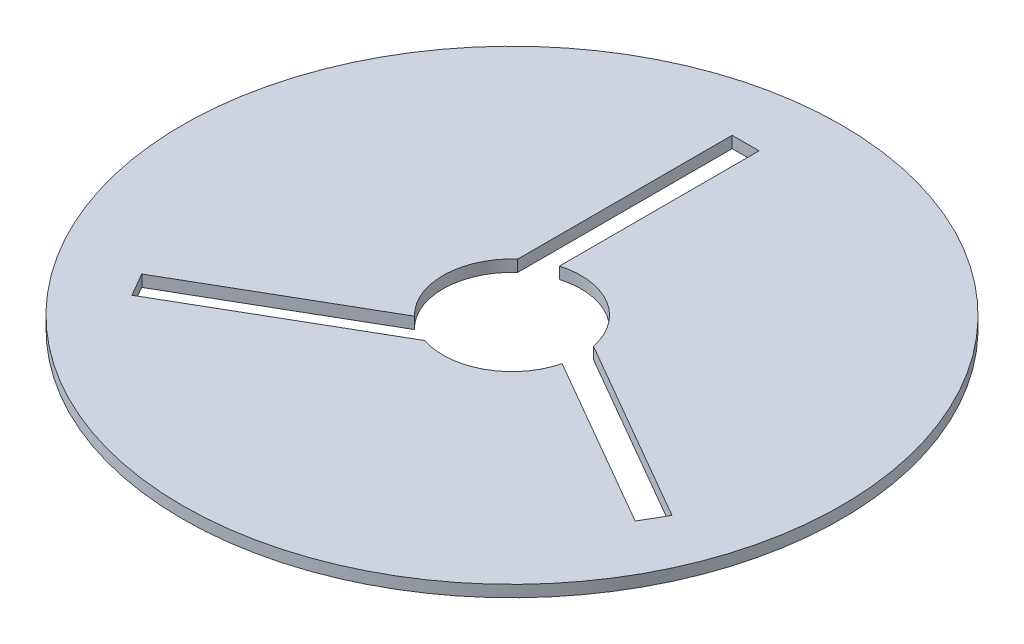
SolidWorks part; units mm, degrees
ref_plane "Alzado" through (0, 0, 0) normal (0, 0, 1) x (1, 0, 0)
ref_plane "Planta" through (0, 0, 0) normal (0, 1, 0) x (1, 0, 0)
ref_plane "Vista lateral" through (0, 0, 0) normal (1, 0, 0) x (0, 0, -1)
sketch "Croquis2" plane through (0, 0, 0) normal (0, 1, 0) x (1, 0, 0)
  line L0 (-11.524, 68.3) -> (-11.524, -4.4)
  line L1 (-11.724, -4.2) -> (-4.974, -4.2)
  line L2 (-5.174, -4.4) -> (-5.174, 68.3)
  line L3 (-5.174, 68.3) -> (-11.524, 68.3)
  line L4 (64.9115, -24.1699) -> (1.9515, 12.1801)
  line L5 (2.2247, 12.2533) -> (-1.1503, 6.4076)
  line L6 (-1.2235, 6.6808) -> (61.7365, -29.6692)
  line L7 (61.7365, -29.6692) -> (64.9115, -24.1699)
  line L8 (-53.3875, -44.1301) -> (9.5725, -7.7801)
  line L9 (-12.0434, -12.6967) -> (6.2975, -2.1076)
  line L10 (6.2975, -2.1076) -> (9.6725, -7.9533)
  line L11 (9.6725, -7.9533) -> (-5.3896, -16.6494)
  line L12 (17.0174, -4.0815) -> (-1.3235, 6.5076)
  line L13 (-1.3235, 6.5076) -> (2.0515, 12.3533)
  line L14 (2.0515, 12.3533) -> (17.1136, 3.6571)
  line L15 (-4.974, 16.7782) -> (-4.974, -4.4)
  line L16 (-4.974, -4.4) -> (-11.724, -4.4)
  line L17 (-11.724, -4.4) -> (-11.724, 12.9922)
  line L18 (9.4993, -8.0533) -> (6.1243, -2.2076)
  line L19 (6.3975, -2.2808) -> (-56.5625, -38.6308)
  line L20 (-56.5625, -38.6308) -> (-53.3875, -44.1301)
  line L21 (-8.349, 3.8) -> (-8.349, -4.2) construction
  line L22 (0.5372, 9.3304) -> (7.4654, 5.3304) construction
  line L23 (0.8836, -9.1304) -> (7.8118, -5.1304) construction
  line L24 (-8.349, 3.8) -> (-5.174, 3.8) construction
  line L25 (7.4654, 5.3304) -> (9.0529, 8.0801) construction
  line L26 (0.8836, -9.1304) -> (2.4711, -11.8801) construction
  circle A0 centre (-8.349, 3.8) radius 1.625
  circle A1 centre (0.8836, -9.1304) radius 1.625
  circle A2 centre (7.4654, 5.3304) radius 1.625
  arc A3 (-5.174, 16.7177) -> (-11.8909, -12.8396) centre (0, 0) ccw
  arc A4 (-11.8909, -12.8396) -> (17.0649, -3.878) centre (0, 0) ccw
  arc A5 (17.0649, -3.878) -> (-5.174, 16.7177) centre (0, 0) ccw
sketch "Croquis3" plane through (0, 0, 0) normal (0, 1, 0) x (1, 0, 0)
  line L0 (-5.174, -4.4) -> (-5.174, 68.3) construction
  line L1 (-5.174, 16.7177) -> (-5.174, 68.3)
  line L2 (-11.524, 68.3) -> (-11.524, -4.4) construction
  line L3 (-5.174, 68.3) -> (-11.524, 68.3) construction
  line L4 (-11.524, 68.3) -> (-11.524, 13.17)
  line L5 (-5.174, 68.3) -> (-11.524, 68.3)
  line L6 (61.7365, -29.6692) -> (64.9115, -24.1699) construction
  line L7 (64.9115, -24.1699) -> (1.9515, 12.1801) construction
  line L8 (-1.2235, 6.6808) -> (61.7365, -29.6692) construction
  line L9 (-56.5625, -38.6308) -> (-53.3875, -44.1301) construction
  line L10 (-53.3875, -44.1301) -> (9.5725, -7.7801) construction
  line L11 (6.3975, -2.2808) -> (-56.5625, -38.6308) construction
  line L12 (61.7365, -29.6692) -> (64.9115, -24.1699)
  line L13 (64.9115, -24.1699) -> (17.1675, 3.3951)
  line L14 (17.0649, -3.878) -> (61.7365, -29.6692)
  line L15 (-56.5625, -38.6308) -> (-53.3875, -44.1301)
  line L16 (-53.3875, -44.1301) -> (-5.6435, -16.565)
  line L17 (-11.8909, -12.8396) -> (-56.5625, -38.6308)
  line L18 (-4.874, 16.8076) -> (-4.874, 68.6)
  line L19 (-4.874, 68.6) -> (-11.824, 68.6)
  line L20 (-11.824, 68.6) -> (-11.824, 12.9013)
  line L21 (-11.824, 68.6) -> (-11.824, 13.17) construction
  line L22 (-12.1188, -12.6248) -> (-56.9724, -38.521)
  line L23 (-56.9724, -38.521) -> (-53.4974, -44.5399)
  line L24 (-53.4974, -44.5399) -> (-5.2609, -16.6905)
  line L25 (16.9928, -4.1828) -> (61.8463, -30.079)
  line L26 (61.8463, -30.079) -> (65.3213, -24.0601)
  line L27 (65.3213, -24.0601) -> (17.0848, 3.7892)
  line L28 (-53.4974, -44.5399) -> (-5.4935, -16.8248) construction
  line L29 (65.3213, -24.0601) -> (17.3175, 3.6549) construction
  line L30 (16.9149, -4.1378) -> (61.8463, -30.079) construction
  line L31 (-12.0409, -12.5798) -> (-56.9724, -38.521) construction
  line L32 (-4.874, 16.7177) -> (-4.874, 68.6) construction
  circle A0 centre (0, 0) radius 85
  arc A1 (-11.8909, -12.8396) -> (17.0649, -3.878) centre (0, 0) ccw construction
  arc A2 (17.0649, -3.878) -> (-5.174, 16.7177) centre (0, 0) ccw construction
  arc A3 (-5.174, 16.7177) -> (-11.8909, -12.8396) centre (0, 0) ccw construction
  arc A4 (-11.8909, -12.8396) -> (17.0649, -3.878) centre (0, 0) ccw
  arc A5 (17.0649, -3.878) -> (-5.174, 16.7177) centre (0, 0) ccw
  arc A6 (-5.174, 16.7177) -> (-11.8909, -12.8396) centre (0, 0) ccw
  arc A7 (17.3574, -3.9445) -> (-4.874, 17.1197) centre (0, 0) ccw
  arc A8 (-11.824, 13.3054) -> (-12.0948, -13.0597) centre (0, 0) ccw
  arc A9 (-12.0948, -13.0597) -> (17.3574, -3.9445) centre (0, 0) ccw
  arc A10 (-5.2627, 17.0042) -> (-12.0948, -13.0597) centre (0, 0) ccw construction
  arc A11 (17.3574, -3.9445) -> (-5.2627, 17.0042) centre (0, 0) ccw construction
  dimension "D1" = 170
  dimension "D2" = 0.3
  dimension "D3" = 0.3
  dimension "D4" = 0.3
  dimension "D5" = 0.3
extrude "Saliente-Extruir1" add sketch "Croquis3" along normal blind 3 contours A0 A9 L24 L23 L22 A8 L20 L19 L18 A7 L27 L26 L25
